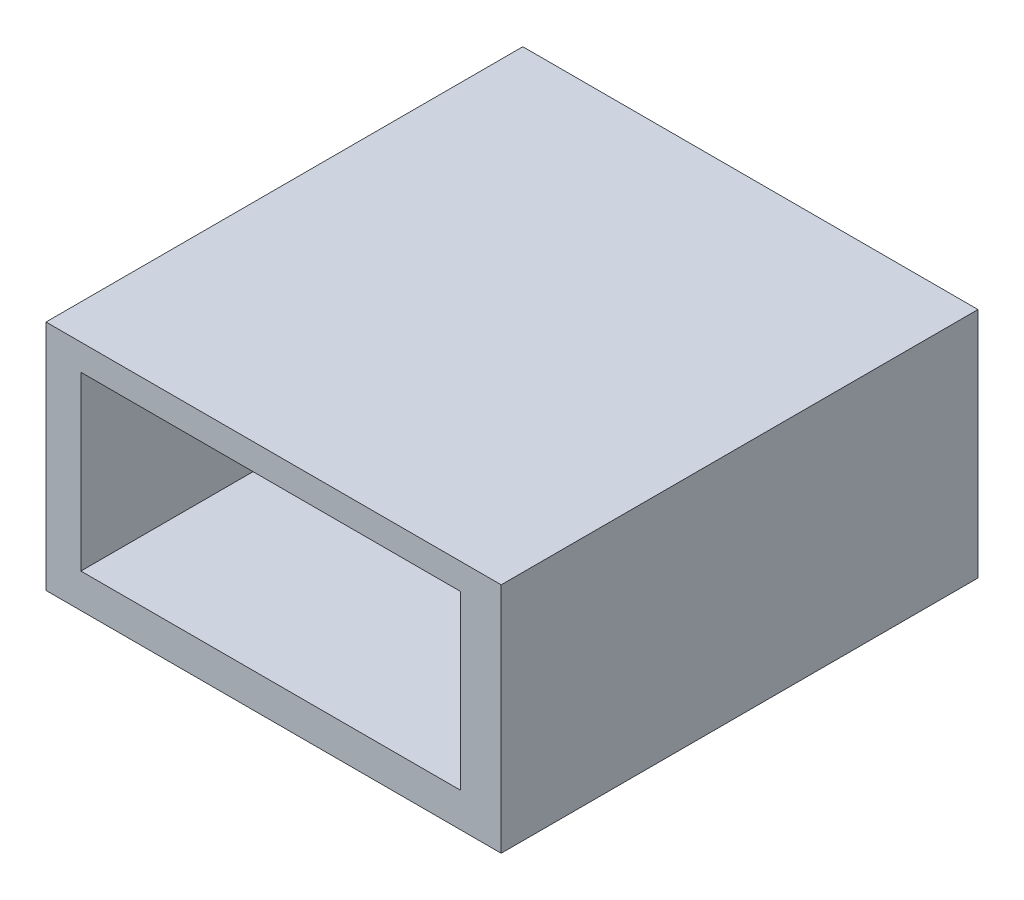
SolidWorks part; units mm, degrees
ref_plane "Front Plane" through (0, 0, 0) normal (0, 0, 1) x (1, 0, 0)
ref_plane "Top Plane" through (0, 0, 0) normal (0, 1, 0) x (1, 0, 0)
ref_plane "Right Plane" through (0, 0, 0) normal (1, 0, 0) x (0, 0, -1)
sketch "Sketch1" plane through (0, 0, 0) normal (0, 0, 1) x (1, 0, 0)
  line L1 (70.397, 29.0173) -> (-72.8008, 29.0173)
  line L2 (70.397, 29.0173) -> (70.397, -44.1269)
  line L3 (70.397, -44.1269) -> (-72.8008, -44.1269)
  line L4 (-72.8008, 29.0173) -> (-72.8008, -44.1269)
extrude "Boss-Extrude1" add sketch "Sketch1" along normal blind 150
sketch "Sketch2" plane through (0, 0, 150) normal (0, 0, 1) x (1, 0, 0)
  line L1 (57.6601, 20.8179) -> (-61.8239, 20.8179)
  line L2 (57.6601, 20.8179) -> (57.6601, -33.3508)
  line L3 (57.6601, -33.3508) -> (-61.8239, -33.3508)
  line L4 (-61.8239, 20.8179) -> (-61.8239, -33.3508)
  point P4 (57.6601, 20.8179)
  point P5 (0, 0)
  point P6 (0, 0)
extrude "Cut-Extrude1" cut sketch "Sketch2" against normal blind 130
